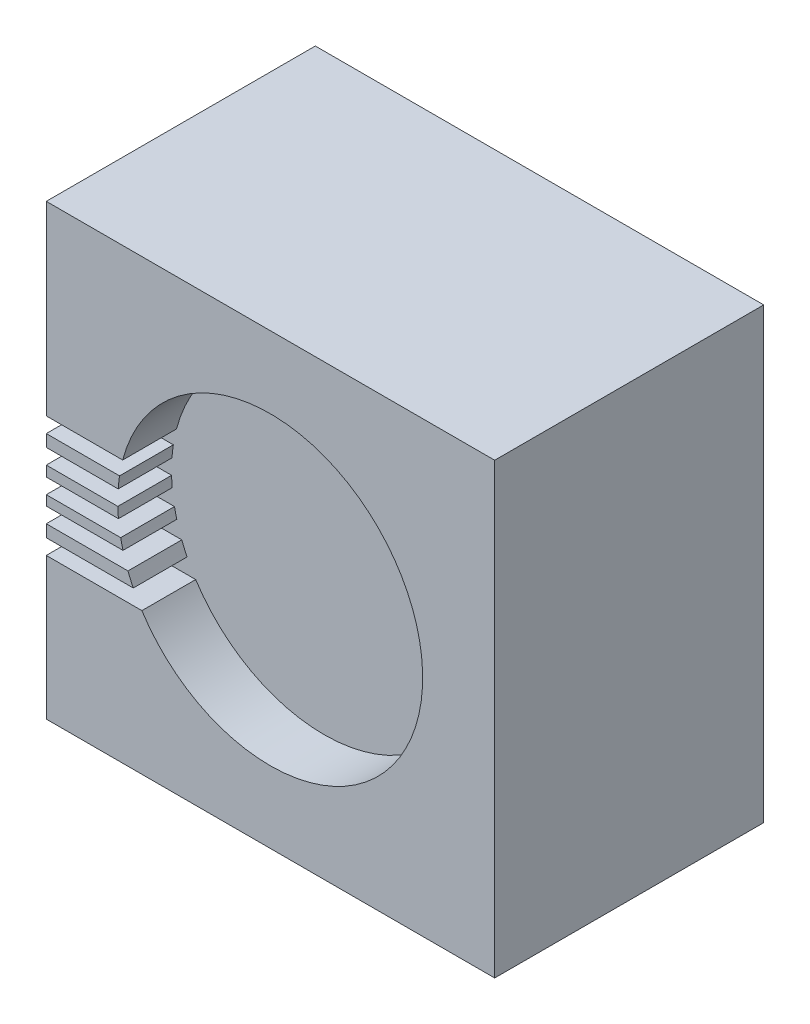
SolidWorks part; units mm, degrees
ref_plane "Front Plane" through (0, 0, 0) normal (0, 0, 1) x (1, 0, 0)
ref_plane "Top Plane" through (0, 0, 0) normal (0, 1, 0) x (1, 0, 0)
ref_plane "Right Plane" through (0, 0, 0) normal (1, 0, 0) x (0, 0, -1)
sketch "Sketch5" plane through (0, 0, 0) normal (0, 0, 1) x (1, 0, 0)
  line L5 (-12.4853, 12.5073) -> (12.5147, 12.5073)
  line L6 (-12.4853, 12.5073) -> (-12.4853, -12.4927)
  line L7 (-12.4853, -12.4927) -> (12.5147, -12.4927)
  line L8 (12.5147, 12.5073) -> (12.5147, -12.4927)
  line L9 (-12.4853, 12.5073) -> (12.5147, -12.4927) construction
  line L10 (-12.4853, -12.4927) -> (12.5147, 12.5073) construction
  point P4 (0.0147, 0.0073)
  dimension "D1" = 25
  dimension "D2" = 25
extrude "Boss-Extrude3" add sketch "Sketch5" along normal blind 15
sketch "Sketch6" plane through (0, 0, 15) normal (0, 0, 1) x (1, 0, 0)
  line L1 (-8.2245, 2.1465) -> (-12.666, 2.1465)
  line L2 (-8.2245, 2.1465) -> (-8.2245, 1.295)
  line L3 (-8.2245, 1.295) -> (-12.666, 1.295)
  line L4 (-12.666, 2.1465) -> (-12.666, 1.295)
  line L5 (-8.2245, 2.1465) -> (-12.666, 1.295) construction
  line L6 (-8.2245, 1.295) -> (-12.666, 2.1465) construction
  line L7 (-8.2539, 0.6249) -> (-12.666, 0.6249)
  line L8 (-8.2539, 0.6249) -> (-8.2539, -0.2266)
  line L9 (-8.2539, -0.2266) -> (-12.666, -0.2266)
  line L10 (-12.666, 0.6249) -> (-12.666, -0.2266)
  line L11 (-8.2539, 0.6249) -> (-12.666, -0.2266) construction
  line L12 (-8.2539, -0.2266) -> (-12.666, 0.6249) construction
  line L13 (-8.2136, -0.8044) -> (-12.689, -0.8044)
  line L14 (-8.2136, -0.8044) -> (-8.2136, -1.656)
  line L15 (-8.2136, -1.656) -> (-12.689, -1.656)
  line L16 (-12.689, -0.8044) -> (-12.689, -1.656)
  line L17 (-8.2136, -0.8044) -> (-12.689, -1.656) construction
  line L18 (-8.2136, -1.656) -> (-12.689, -0.8044) construction
  line L19 (-7.8512, -2.2081) -> (-12.689, -2.2081)
  line L20 (-7.8512, -2.2081) -> (-7.8512, -3.0596)
  line L21 (-7.8512, -3.0596) -> (-12.689, -3.0596)
  line L22 (-12.689, -2.2081) -> (-12.689, -3.0596)
  line L23 (-7.8512, -2.2081) -> (-12.689, -3.0596) construction
  line L24 (-7.8512, -3.0596) -> (-12.689, -2.2081) construction
  line L25 (-7.1076, -3.7371) -> (-12.7121, -3.7371)
  line L26 (-7.1076, -3.7371) -> (-7.1076, -4.5886)
  line L27 (-7.1076, -4.5886) -> (-12.7121, -4.5886)
  line L28 (-12.7121, -3.7371) -> (-12.7121, -4.5886)
  line L29 (-7.1076, -3.7371) -> (-12.7121, -4.5886) construction
  line L30 (-7.1076, -4.5886) -> (-12.7121, -3.7371) construction
  circle A0 centre (0, 0) radius 8.5
  point P7 (-10.4452, 1.7208)
  point P13 (-10.4599, 0.1992)
  point P18 (-10.4513, -1.2302)
  point P23 (-10.2701, -2.6338)
  point P28 (-9.9099, -4.1628)
  dimension "D1" = 17
extrude "Cut-Extrude3" cut sketch "Sketch6" against normal blind 3 contours L4 L3 L2 L1 | L10 L9 L8 L7 | L16 L15 L14 L13 | L22 L21 L20 L19 | L28 L27 L26 L25 | A0
